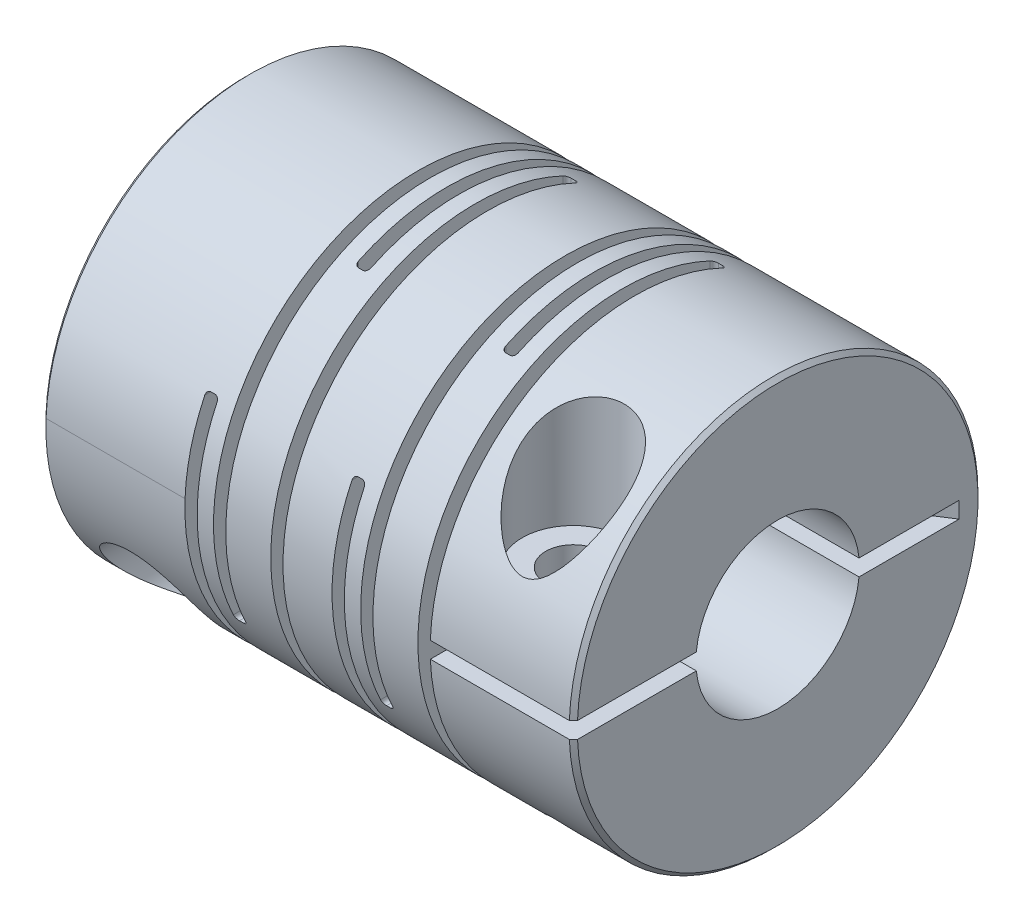
SolidWorks part; units mm, degrees
ref_plane "Front Plane" through (0, 0, 0) normal (0, 0, 1) x (1, 0, 0)
ref_plane "Top Plane" through (0, 0, 0) normal (0, 1, 0) x (1, 0, 0)
ref_plane "Right Plane" through (0, 0, 0) normal (1, 0, 0) x (0, 0, -1)
ref_plane "Plane1" through (0, 0, 10) normal (0, 0, 1) x (1, 0, 0)
ref_plane "Plane2" through (0, 10, 0) normal (0, 1, 0) x (1, 0, 0)
ref_plane "Plane3" through (26, 0, 0) normal (1, 0, 0) x (0, 0, -1)
sketch "Sketch1" plane through (0, 0, 0) normal (0, 0, 1) x (1, 0, 0)
  line L0 (0, 0) -> (26, 0) construction
  line L1 (0, 0) -> (26, 0)
  line L3 (0, 0) -> (0, 10)
  line L4 (0, 10) -> (26, 10)
  line L5 (26, 0) -> (26, 10)
  dimension "L" = 26
  dimension "D" = 20
revolve "Revolve1" add sketch "Sketch1" about L0
sketch "Sketch2" plane through (0, 0, 10) normal (0, 0, 1) x (1, 0, 0)
  line L0 (16.2, 10) -> (16.2, -4.3)
  line L1 (15.6, -4.3) -> (15.6, 10)
  line L2 (15.8, -4.5) -> (16, -4.5)
  line L3 (14.8, 4.3) -> (14.8, -10)
  line L4 (14.6, 4.5) -> (14.4, 4.5)
  line L5 (14.2, -10) -> (14.2, 4.3)
  line L6 (9, 10) -> (9, -4.3)
  line L7 (8.6, -4.5) -> (8.8, -4.5)
  line L8 (8.4, -4.3) -> (8.4, 10)
  line L9 (7.6, 4.3) -> (7.6, -10)
  line L10 (7.4, 4.5) -> (7.2, 4.5)
  line L11 (7, -10) -> (7, 4.3)
  line L12 (8.4, 10) -> (9, 10)
  line L13 (7, -10) -> (7.6, -10)
  line L14 (14.2, -10) -> (14.8, -10)
  line L15 (15.6, 10) -> (16.2, 10)
  line L16 (0, 0) -> (26, 0) construction
  line L17 (26, -8.8) -> (26, 8.8) construction
  arc A0 (16, -4.5) -> (16.2, -4.3) centre (16, -4.3) ccw
  arc A1 (15.6, -4.3) -> (15.8, -4.5) centre (15.8, -4.3) ccw
  arc A2 (14.8, 4.3) -> (14.6, 4.5) centre (14.6, 4.3) ccw
  arc A3 (14.4, 4.5) -> (14.2, 4.3) centre (14.4, 4.3) ccw
  arc A4 (8.8, -4.5) -> (9, -4.3) centre (8.8, -4.3) ccw
  arc A5 (8.4, -4.3) -> (8.6, -4.5) centre (8.6, -4.3) ccw
  arc A6 (7.6, 4.3) -> (7.4, 4.5) centre (7.4, 4.3) ccw
  arc A7 (7.2, 4.5) -> (7, 4.3) centre (7.2, 4.3) ccw
  dimension "FIX_3" = 0.2
  dimension "FIX_1" = 10
  dimension "D" = 20
  dimension "L_s" = 7
  dimension "MSM_1" = 4.3
  dimension "MSM_2" = 9.8
  dimension "MSM_4" = 0.6
extrude "Cut-Extrude1" cut sketch "Sketch2" against normal through all
sketch "Sketch3" plane through (0, 10, 0) normal (0, 1, 0) x (1, 0, 0)
  line L0 (17.6, 10) -> (17.6, -4.3)
  line L1 (17, -4.3) -> (17, 10)
  line L2 (17.2, -4.5) -> (17.4, -4.5)
  line L3 (19, 4.3) -> (19, -10)
  line L4 (18.8, 4.5) -> (18.6, 4.5)
  line L5 (18.4, -10) -> (18.4, 4.3)
  line L6 (10.4, 10) -> (10.4, -4.3)
  line L7 (10, -4.5) -> (10.2, -4.5)
  line L8 (9.8, -4.3) -> (9.8, 10)
  line L9 (11.8, 4.3) -> (11.8, -10)
  line L10 (11.6, 4.5) -> (11.4, 4.5)
  line L11 (11.2, -10) -> (11.2, 4.3)
  line L12 (9.8, 10) -> (10.4, 10)
  line L13 (11.2, -10) -> (11.8, -10)
  line L14 (18.4, -10) -> (19, -10)
  line L15 (17, 10) -> (17.6, 10)
  line L16 (0, 0) -> (26, 0) construction
  line L17 (26, -8.8) -> (26, 8.8) construction
  arc A0 (17.4, -4.5) -> (17.6, -4.3) centre (17.4, -4.3) ccw
  arc A1 (17, -4.3) -> (17.2, -4.5) centre (17.2, -4.3) ccw
  arc A2 (19, 4.3) -> (18.8, 4.5) centre (18.8, 4.3) ccw
  arc A3 (18.6, 4.5) -> (18.4, 4.3) centre (18.6, 4.3) ccw
  arc A4 (10.2, -4.5) -> (10.4, -4.3) centre (10.2, -4.3) ccw
  arc A5 (9.8, -4.3) -> (10, -4.5) centre (10, -4.3) ccw
  arc A6 (11.8, 4.3) -> (11.6, 4.5) centre (11.6, 4.3) ccw
  arc A7 (11.4, 4.5) -> (11.2, 4.3) centre (11.4, 4.3) ccw
  dimension "FIX_4" = 0.2
  dimension "FIX_1" = 10
  dimension "D" = 20
  dimension "L_s" = 7
  dimension "MSM_1" = 4.3
  dimension "MSM_2" = 9.8
  dimension "MSM_4" = 0.6
extrude "Cut-Extrude2" cut sketch "Sketch3" against normal through all
chamfer "Chamfer1" distance 0.2 2 edges at (26, 0, 10) (0, 0, 10)
sketch "Sketch4" plane through (0, 0, 0) normal (0, 0, 1) x (1, 0, 0)
  line L1 (0, 0) -> (25.1364, 0) construction
  line L2 (7.3, -10) -> (-7.7, -10)
  line L3 (-7.7, -10) -> (-7.7, 11)
  line L4 (7.3, -4) -> (7.3, -10)
  line L6 (-7.7, 11) -> (7.3, 11) construction
  line L7 (7.3, 11) -> (7.3, -10) construction
  arc A1 (7.3, -4) -> (-7.7, 11) centre (-7.7, -4) ccw
  dimension "FIX_1" = 10
  dimension "MSM_5" = 15
  dimension "MSM_6" = 7.3
  dimension "MSM_7" = 6
extrude "Cut-Extrude3" cut sketch "Sketch4" against normal mid plane 0.8
sketch "Sketch5" plane through (0, 0, 0) normal (0, 1, 0) x (1, 0, 0)
  line L0 (18.7, -10) -> (33.7, -10)
  line L1 (33.7, -10) -> (33.7, 11)
  line L2 (18.7, -4) -> (18.7, -10)
  line L3 (33.7, 11) -> (18.7, 11) construction
  line L4 (18.7, 11) -> (18.7, -10) construction
  line L5 (0, 0) -> (26, 0) construction
  line L6 (26, -8.8) -> (26, 8.8) construction
  arc A0 (33.7, 11) -> (18.7, -4) centre (33.7, -4) ccw
  dimension "FIX_1" = 10
  dimension "MSM_5" = 15
  dimension "MSM_6" = 7.3
  dimension "MSM_7" = 6
extrude "Cut-Extrude4" cut sketch "Sketch5" against normal mid plane 0.8
hole_wizard "Socket Head Cap Screw1" positions "Sketch8" profile "Sketch7" counterbore size "M2.5" standard "JIS"
sketch "Sketch8" plane through (0, 0, 10) normal (0, 0, 1) x (1, 0, 0)
  point P0 (3.5, -6.5)
  dimension "A" = 6.5
  dimension "F" = 3.5
sketch "Sketch7" plane through (3.5, -6.5, 10) normal (1, 0, 0) x (0, -1, 0)
  line L0 (0, 0) -> (0, 9.6)
  line L1 (0, 9.6) -> (1.35, 9.6)
  line L3 (1.35, 9.6) -> (1.35, 6.5)
  line L4 (1.35, 6.5) -> (2.5, 6.5)
  line L5 (2.5, 6.5) -> (2.5, 0)
  line L7 (2.5, 0) -> (0, 0)
  line L11 (0, 0) -> (0, 9.6) construction
  dimension "Thru Hole Depth" = 9.6
  dimension "MSM_8" = 5
  dimension "MSM_9" = 2.7
  dimension "MSM_10" = 6.5
hole_wizard "Tap1" positions "Sketch10" profile "Sketch9" hole size "M2x0.4" standard "JIS" end condition through all
sketch "Sketch10" plane through (0, 0, -0.4) normal (0, 0, 1) x (1, 0, 0)
  point P0 (3.5, -6.5)
  dimension "A" = 6.5
  dimension "F" = 3.5
sketch "Sketch9" plane through (3.5, -6.5, -0.4) normal (1, 0, 0) x (0, -1, 0)
  line L0 (0, 0) -> (0, 9.6)
  line L1 (0, 9.6) -> (1.0065, 9.6)
  line L2 (1.0065, 9.6) -> (1.0065, 0)
  line L5 (1.0065, 0) -> (0, 0)
  line L11 (0, 0) -> (0, 9.6) construction
  dimension "Thru Hole Depth" = 9.6
  dimension "STD" = 2.013
cosmetic thread "Thread1" parameters "M"=2.5
hole_wizard "Socket Head Cap Screw2" positions "Sketch12" profile "Sketch11" counterbore size "M2.5" standard "JIS"
sketch "Sketch12" plane through (0, 10, 0) normal (0, 1, 0) x (1, 0, 0)
  line L4 (26, -8.8) -> (26, 8.8) construction
  point P0 (22.5, -6.5)
  dimension "A" = 6.5
  dimension "F" = 3.5
sketch "Sketch11" plane through (22.5, 10, 6.5) normal (1, 0, 0) x (0, 0, 1)
  line L0 (0, 0) -> (0, 9.6)
  line L1 (0, 9.6) -> (1.35, 9.6)
  line L3 (1.35, 9.6) -> (1.35, 6.5)
  line L4 (1.35, 6.5) -> (2.5, 6.5)
  line L5 (2.5, 6.5) -> (2.5, 0)
  line L7 (2.5, 0) -> (0, 0)
  line L11 (0, 0) -> (0, 9.6) construction
  dimension "Thru Hole Depth" = 9.6
  dimension "MSM_8" = 5
  dimension "MSM_9" = 2.7
  dimension "MSM_10" = 6.5
hole_wizard "Tap2" positions "Sketch14" profile "Sketch13" hole size "M2x0.4" standard "JIS" end condition through all
sketch "Sketch14" plane through (0, -0.4, 0) normal (0, 1, 0) x (1, 0, 0)
  line L0 (26, -8.8) -> (26, 8.8) construction
  point P0 (22.5, -6.5)
  dimension "A" = 6.5
  dimension "F" = 3.5
sketch "Sketch13" plane through (22.5, -0.4, 6.5) normal (1, 0, 0) x (0, 0, 1)
  line L0 (0, 0) -> (0, 9.6)
  line L1 (0, 9.6) -> (1.0065, 9.6)
  line L2 (1.0065, 9.6) -> (1.0065, 0)
  line L5 (1.0065, 0) -> (0, 0)
  line L11 (0, 0) -> (0, 9.6) construction
  dimension "Thru Hole Depth" = 9.6
  dimension "STD" = 2.013
cosmetic thread "Thread2" parameters "M"=2.5
sketch "Sketch15" plane through (0, 0, 0) normal (0, 0, 1) x (1, 0, 0)
  line L0 (0, 0) -> (26, 0) construction
  line L1 (26, -8.8) -> (26, 8.8) construction
  line L2 (7, -10) -> (7, 4.3) construction
  line L3 (0, 0) -> (26, 0) construction
  line L4 (7, 0) -> (7, 3.25)
  line L5 (7, 3.25) -> (19, 3.25)
  line L6 (19, 0) -> (19, 3.25)
  line L7 (7, 0) -> (19, 0)
  dimension "FIX_9" = 6.5
revolve "Cut-Revolve1" [suppressed] cut sketch "Sketch15" about L0
sketch "Sketch16" plane through (0, 0, 0) normal (0, 0, 1) x (1, 0, 0)
  line L0 (0, 0.0041) -> (26, 0.0041) construction
  line L1 (0, 9.8) -> (0, -9.7918) construction
  line L2 (26, -8.8) -> (26, 8.8) construction
  line L3 (7, 0.0041) -> (7, 4.0041)
  line L4 (7, 4.0041) -> (19, 4.0041)
  line L5 (19, 4.0041) -> (19, 0.0041)
  line L6 (7, -10) -> (7, 4.3) construction
  line L7 (7, 0.0041) -> (19, 0.0041)
  dimension "D2_s" = 8
revolve "Cut-Revolve2" cut sketch "Sketch16" about L0
sketch "Sketch17" plane through (0, 0, 0) normal (1, 0, 0) x (0, 0, -1)
  circle A0 centre (0, 0) radius 3
  dimension "D1_s" = 6
extrude "Cut-Extrude5" cut sketch "Sketch17" along normal up to surface (7 mm away)
sketch "Sketch18" plane through (26, 0, 0) normal (1, 0, 0) x (0, 0, -1)
  circle A0 centre (0, 0) radius 4
  dimension "D2_s" = 8
extrude "Cut-Extrude6" cut sketch "Sketch18" against normal up to surface (7 mm away)
equation "\"FIX_1@Plane1\"= \"D@Sketch1\" / 2"
equation "\"FIX_9@Sketch15\"= \"D1_s@Sketch17\" + 0.5"
equation "\"Cut-Revolve1\" = if ( \"D1_s@Sketch17\" = \"D2_s@Sketch18\" , \"unsuppressed\" , \"suppressed\" )"
equation "\"Cut-Revolve2\" = if ( \"D1_s@Sketch17\" < > \"D2_s@Sketch18\" , \"unsuppressed\" , \"suppressed\" )"
